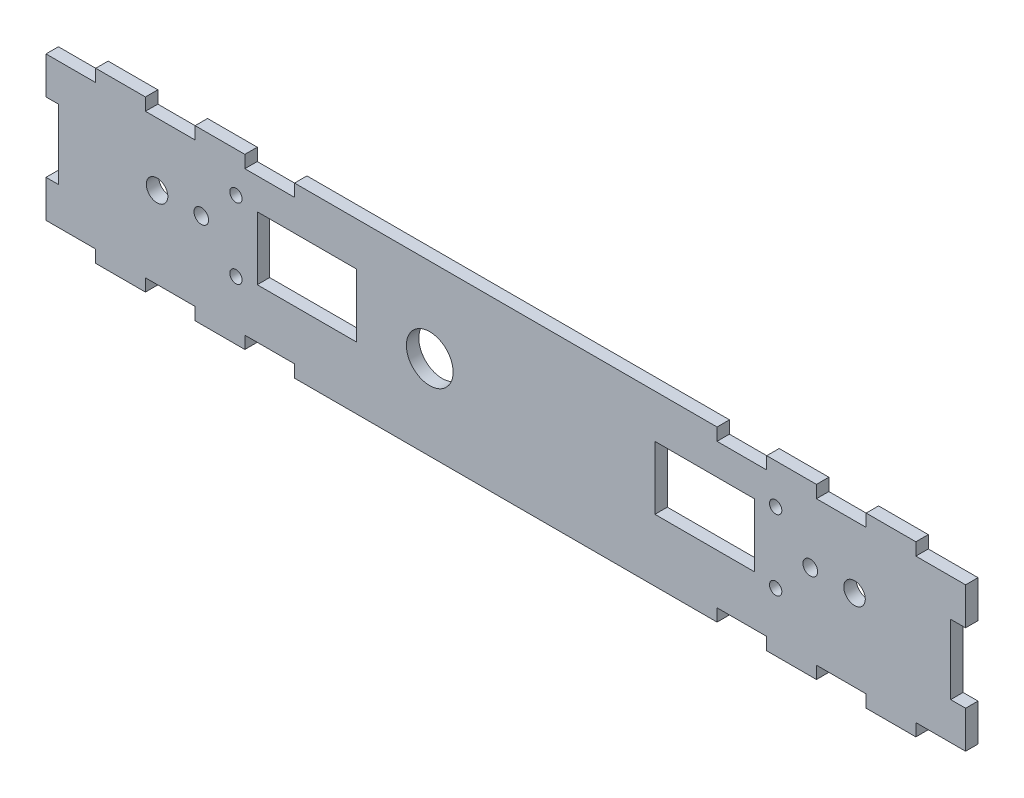
SolidWorks part; units mm, degrees
material "Acrylic (Medium-high impact)"
ref_plane "Front Plane" through (0, 0, 0) normal (0, 0, 1) x (1, 0, 0)
ref_plane "Top Plane" through (0, 0, 0) normal (0, 1, 0) x (1, 0, 0)
ref_plane "Right Plane" through (0, 0, 0) normal (1, 0, 0) x (0, 0, -1)
sketch "Sketch3" plane through (0, 0, 0) normal (0, 0, 1) x (1, 0, 0)
  line L0 (0, 22.5) -> (0, 0)
  line L1 (0, 0) -> (31.6, 0)
  line L2 (36.6, 5) -> (36.6, 17.5)
  line L3 (31.6, 22.5) -> (0, 22.5)
  line L4 (0, 0) -> (-63.5, 0) construction
  line L5 (-63.5, 0) -> (-63.5, 28.85) construction
  line L6 (-158.6, 22.5) -> (-127, 22.5)
  line L7 (0, 22.5) -> (-25.4, 22.5)
  line L8 (0, 22.5) -> (0, 0)
  line L9 (0, 0) -> (-25.4, 0)
  line L10 (-25.4, 22.5) -> (-25.4, 0)
  line L11 (-163.6, 5) -> (-163.6, 17.5)
  line L12 (-127, 0) -> (-158.6, 0)
  line L13 (-127, 22.5) -> (-127, 0)
  line L14 (-127, 0) -> (-101.6, 0)
  line L15 (-101.6, 22.5) -> (-101.6, 0)
  line L16 (-127, 22.5) -> (-101.6, 22.5)
  line L17 (-127, 22.5) -> (-127, 0)
  line L18 (-180.975, 28.85) -> (-180.975, -6.3925)
  line L21 (20.8125, -11.155) -> (58.7375, -11.155)
  line L22 (58.7375, 0) -> (58.7375, -11.155)
  line L25 (-179.3875, 28.85) -> (-185.7375, 28.85)
  line L26 (-185.7375, 22.5) -> (-185.7375, 28.85)
  line L27 (-185.7375, 28.85) -> (58.7375, 28.85)
  line L28 (-185.7375, 28.85) -> (-185.7375, -11.155)
  line L29 (-185.7375, -11.155) -> (58.7375, -11.155)
  line L30 (58.7375, 28.85) -> (58.7375, -11.155)
  line L31 (-180.975, -6.3925) -> (58.7375, -6.3925)
  line L32 (-185.7375, 24.0875) -> (53.975, 24.0875)
  line L33 (53.975, 24.0875) -> (53.975, -11.155)
  line L35 (-127, 22.5) -> (-101.6, 22.5)
  line L36 (-127, 22.5) -> (-127, 19.325)
  line L37 (-127, 19.325) -> (-101.6, 19.325)
  line L38 (-101.6, 22.5) -> (-101.6, 19.325)
  line L39 (-127, 0) -> (-101.6, 0)
  line L40 (-127, 0) -> (-127, 3.175)
  line L41 (-127, 3.175) -> (-101.6, 3.175)
  line L42 (-101.6, 0) -> (-101.6, 3.175)
  line L43 (0, 22.5) -> (-25.4, 22.5)
  line L44 (0, 22.5) -> (0, 19.325)
  line L45 (0, 19.325) -> (-25.4, 19.325)
  line L46 (-25.4, 22.5) -> (-25.4, 19.325)
  line L47 (0, 0) -> (-25.4, 0)
  line L48 (0, 0) -> (0, 3.175)
  line L49 (0, 3.175) -> (-25.4, 3.175)
  line L50 (-25.4, 0) -> (-25.4, 3.175)
  circle A2 centre (5.45, 2.25) radius 1.575
  circle A3 centre (5.45, 20.25) radius 1.575
  arc A6 (31.6, 0) -> (36.6, 5) centre (31.6, 5) ccw
  arc A7 (36.6, 17.5) -> (31.6, 22.5) centre (31.6, 17.5) ccw
  arc A8 (22.85, 11.25) -> (28.35, 11.25) centre (25.6, 11.25) ccw
  arc A9 (28.35, 11.25) -> (22.85, 11.25) centre (25.6, 11.25) ccw
  arc A10 (12.425, 11.25) -> (16.175, 11.25) centre (14.3, 11.25) ccw
  arc A11 (16.175, 11.25) -> (12.425, 11.25) centre (14.3, 11.25) ccw
  arc A12 (-143.175, 11.25) -> (-139.425, 11.25) centre (-141.3, 11.25) cw
  arc A13 (-139.425, 11.25) -> (-143.175, 11.25) centre (-141.3, 11.25) cw
  arc A14 (-155.35, 11.25) -> (-149.85, 11.25) centre (-152.6, 11.25) cw
  arc A15 (-149.85, 11.25) -> (-155.35, 11.25) centre (-152.6, 11.25) cw
  arc A16 (-163.6, 17.5) -> (-158.6, 22.5) centre (-158.6, 17.5) cw
  arc A17 (-158.6, 0) -> (-163.6, 5) centre (-158.6, 5) cw
  circle A18 centre (-132.45, 20.25) radius 1.575
  circle A19 centre (-132.45, 2.25) radius 1.575
  dimension "D3" = 5.45
  dimension "D4" = 3.15
  dimension "D8" = 3.15
  dimension "D6" = 2.25
  dimension "D9" = 1.875
  dimension "D10" = 4.7625
  dimension "D11" = 2.75
  dimension "D12" = 4.7625
  dimension "D17" = 5
  dimension "D18" = 5
  dimension "D1" = 31.6
  dimension "D2" = 36.6
  dimension "D5" = 2.25
  dimension "D7" = 5.45
  dimension "D13" = 11.25
  dimension "D14" = 14.3
  dimension "D15" = 11
  dimension "D16" = 11.25
  dimension "D19" = 22.5
  dimension "D20" = 244.475
  dimension "D21" = 30.48
  dimension "D22" = 25.4
  dimension "D23" = 3.175
  dimension "D24" = 25.4
  dimension "D25" = 3.175
  dimension "D26" = 25.4
extrude "Boss-Extrude1" add sketch "Sketch3" along normal blind 3.175 contours L33 L32 L18 L31 A7 L2 A6 L1 L9 L10 L7 L3 L12 A17 L11 A16 L6 L16 L15 L14 | A17 L12 L13 L6 A16 L11 A18 A12 A13 A14 A15 A19 | L2 A7 L3 L0 L1 A6 A11 A10 A9 A8 A2 A3 | L0 L49 L10 L9 | L45 L0 L7 L10 | L13 L37 L15 L16 | L40 L41 L42 L39
sketch "Sketch4" plane through (0, 0, 3.175) normal (0, 0, 1) x (1, 0, 0)
  line L0 (-155.575, 30.4375) -> (-155.575, 27.2625)
  line L1 (-180.975, 24.0875) -> (53.975, 24.0875)
  line L2 (-180.975, 24.0875) -> (-180.975, 30.4375)
  line L3 (-180.975, 30.4375) -> (53.975, 30.4375)
  line L4 (53.975, -6.3925) -> (53.975, 24.0875)
  line L5 (53.975, 24.0875) -> (-180.975, 24.0875)
  line L6 (-180.975, 24.0875) -> (-180.975, -6.3925)
  line L7 (-180.975, -6.3925) -> (53.975, -6.3925)
  line L8 (53.975, -6.3925) -> (53.975, 24.0875)
  line L9 (53.975, 24.0875) -> (-180.975, 24.0875)
  line L10 (-180.975, 24.0875) -> (-180.975, -6.3925)
  line L11 (-180.975, -6.3925) -> (53.975, -6.3925)
  line L12 (53.975, 24.0875) -> (53.975, 30.4375)
  line L13 (-180.975, 30.4375) -> (53.975, 30.4375)
  line L14 (-180.975, 30.4375) -> (-180.975, 27.2625)
  line L15 (-180.975, 27.2625) -> (53.975, 27.2625)
  line L16 (53.975, 30.4375) -> (53.975, 27.2625)
  line L17 (-180.975, 30.4375) -> (-168.275, 30.4375)
  line L18 (-180.975, 30.4375) -> (-180.975, 27.2625)
  line L19 (-180.975, 27.2625) -> (-168.275, 27.2625)
  line L20 (-168.275, 30.4375) -> (-168.275, 27.2625)
  line L21 (-155.575, 30.4375) -> (-142.875, 30.4375)
  line L22 (-142.875, 30.4375) -> (-142.875, 27.2625)
  line L23 (-155.575, 27.2625) -> (-142.875, 27.2625)
  line L24 (-130.175, 30.4375) -> (-130.175, 27.2625)
  line L25 (-130.175, 30.4375) -> (-117.475, 30.4375)
  line L26 (-117.475, 30.4375) -> (-117.475, 27.2625)
  line L27 (-130.175, 27.2625) -> (-117.475, 27.2625)
  line L28 (28.575, 27.2625) -> (28.575, 30.4375)
  line L29 (53.975, 27.2625) -> (41.275, 27.2625)
  line L30 (53.975, 27.2625) -> (53.975, 30.4375)
  line L31 (53.975, 30.4375) -> (41.275, 30.4375)
  line L32 (41.275, 27.2625) -> (41.275, 30.4375)
  line L33 (28.575, 27.2625) -> (15.875, 27.2625)
  line L34 (15.875, 27.2625) -> (15.875, 30.4375)
  line L35 (28.575, 30.4375) -> (15.875, 30.4375)
  line L36 (3.175, 27.2625) -> (3.175, 30.4375)
  line L37 (3.175, 27.2625) -> (-9.525, 27.2625)
  line L38 (-9.525, 27.2625) -> (-9.525, 30.4375)
  line L39 (3.175, 30.4375) -> (-9.525, 30.4375)
  line L40 (-180.975, 8.8475) -> (49.4654, 8.8475) construction
  line L41 (3.175, -12.7425) -> (-9.525, -12.7425)
  line L42 (-9.525, -9.5675) -> (-9.525, -12.7425)
  line L43 (3.175, -9.5675) -> (-9.525, -9.5675)
  line L44 (3.175, -9.5675) -> (3.175, -12.7425)
  line L45 (28.575, -12.7425) -> (15.875, -12.7425)
  line L46 (15.875, -9.5675) -> (15.875, -12.7425)
  line L47 (28.575, -9.5675) -> (15.875, -9.5675)
  line L48 (41.275, -9.5675) -> (41.275, -12.7425)
  line L49 (53.975, -12.7425) -> (41.275, -12.7425)
  line L50 (53.975, -9.5675) -> (53.975, -12.7425)
  line L51 (53.975, -9.5675) -> (41.275, -9.5675)
  line L52 (28.575, -9.5675) -> (28.575, -12.7425)
  line L53 (-130.175, -9.5675) -> (-117.475, -9.5675)
  line L54 (-117.475, -12.7425) -> (-117.475, -9.5675)
  line L55 (-130.175, -12.7425) -> (-117.475, -12.7425)
  line L56 (-130.175, -12.7425) -> (-130.175, -9.5675)
  line L57 (-155.575, -9.5675) -> (-142.875, -9.5675)
  line L58 (-142.875, -12.7425) -> (-142.875, -9.5675)
  line L59 (-155.575, -12.7425) -> (-142.875, -12.7425)
  line L60 (-168.275, -12.7425) -> (-168.275, -9.5675)
  line L61 (-180.975, -9.5675) -> (-168.275, -9.5675)
  line L62 (-180.975, -12.7425) -> (-180.975, -9.5675)
  line L63 (-180.975, -12.7425) -> (-168.275, -12.7425)
  line L64 (53.975, -12.7425) -> (53.975, -9.5675)
  line L65 (-180.975, -9.5675) -> (53.975, -9.5675)
  line L66 (-180.975, -12.7425) -> (-180.975, -9.5675)
  line L67 (-180.975, -12.7425) -> (53.975, -12.7425)
  line L68 (53.975, -6.3925) -> (53.975, -12.7425)
  line L69 (53.975, -6.3925) -> (-180.975, -6.3925)
  line L70 (-180.975, -12.7425) -> (53.975, -12.7425)
  line L71 (-180.975, -6.3925) -> (-180.975, -12.7425)
  line L72 (-180.975, -6.3925) -> (53.975, -6.3925)
  line L73 (-155.575, -12.7425) -> (-155.575, -9.5675)
  line M29 (53.975, 24.0875) -> (-180.975, 24.0875)
  line M31 (-180.975, -6.3925) -> (53.975, -6.3925)
  dimension "D2" = 6.35
  dimension "D3" = 3.175
  dimension "D4" = 12.7
  dimension "D5" = 3
  dimension "D6" = 12.7
  dimension "D7" = 3
  dimension "D1" = 0
extrude "Boss-Extrude2" add sketch "Sketch4" against normal blind 3.175 contours L15 L38 L13 L26 | L24 L13 L22 L15 | L13 L20 L15 L0 | L15 L2 L12 M29 | L36 L15 L34 L3 | L15 L32 L3 L28 | L71 L61 L65 L57 L53 L43 L47 L51 L68 M31 | L52 L67 L48 L65 | L44 L67 L46 L65 | L54 L67 L42 L65 | L58 L67 L56 L65 | L67 L73 L65 L60
sketch "Sketch5" plane through (0, 0, 3.175) normal (0, 0, 1) x (1, 0, 0)
  line L0 (53.975, 27.2625) -> (53.975, -9.5675) construction
  line L1 (-168.275, -12.7425) -> (-180.975, -12.7425)
  line L2 (-168.275, -12.7425) -> (-168.275, -0.0425)
  line L3 (-168.275, -0.0425) -> (-180.975, -0.0425)
  line L4 (-180.975, -12.7425) -> (-180.975, -0.0425)
  line L5 (-180.975, 27.2625) -> (-180.975, -9.5675) construction
  line L6 (-168.275, 30.4375) -> (-180.975, 30.4375)
  line L7 (-168.275, 30.4375) -> (-168.275, 17.7375)
  line L8 (-168.275, 17.7375) -> (-180.975, 17.7375)
  line L9 (-180.975, 30.4375) -> (-180.975, 17.7375)
  line L10 (41.275, 30.4375) -> (53.975, 30.4375)
  line L11 (41.275, 30.4375) -> (41.275, 17.7375)
  line L12 (41.275, 17.7375) -> (53.975, 17.7375)
  line L13 (53.975, 30.4375) -> (53.975, 17.7375)
  line L15 (41.275, -12.7425) -> (53.975, -12.7425)
  line L16 (41.275, -12.7425) -> (41.275, -0.0425)
  line L17 (41.275, -0.0425) -> (53.975, -0.0425)
  line L18 (53.975, -12.7425) -> (53.975, -0.0425)
  line L19 (-180.975, 17.7375) -> (-177.8, 17.7375)
  line L20 (-180.975, 17.7375) -> (-180.975, -0.0425)
  line L21 (-180.975, -0.0425) -> (-177.8, -0.0425)
  line L22 (-177.8, 17.7375) -> (-177.8, -0.0425)
  line L23 (53.975, 17.7375) -> (50.165, 17.7375)
  line L24 (53.975, 17.7375) -> (53.975, -0.0425)
  line L25 (53.975, -0.0425) -> (50.165, -0.0425)
  line L26 (50.165, 17.7375) -> (50.165, -0.0425)
  dimension "D1" = 12.7
  dimension "D2" = 12.7
  dimension "D3" = 12.7
  dimension "D4" = 3.175
  dimension "D5" = 3.81
extrude "Cut-Extrude1" cut sketch "Sketch5" against normal blind 7.62 contours L22 L8 L20 L3 | L12 L26 L17 L24
sketch "Sketch6" plane through (0, 0, 0) normal (0, 0, -1) x (-1, 0, 0)
  line L0 (180.975, 27.2625) -> (70.612, 27.2625)
  line L1 (180.975, -9.5675) -> (95.25, -9.5675)
  line L3 (95.25, -9.5675) -> (70.612, -9.5675)
  line L4 (95.25, -9.5675) -> (95.25, 27.2625)
  line L5 (95.25, 27.2625) -> (70.612, 27.2625)
  line L6 (70.612, -9.5675) -> (70.612, 27.2625)
  circle A0 centre (82.931, 8.8475) radius 5.969
  dimension "D3" = 11.938
  dimension "D1" = 110.363
  dimension "D2" = 85.725
extrude "Cut-Extrude2" cut sketch "Sketch6" against normal blind 5.08 contours A0
